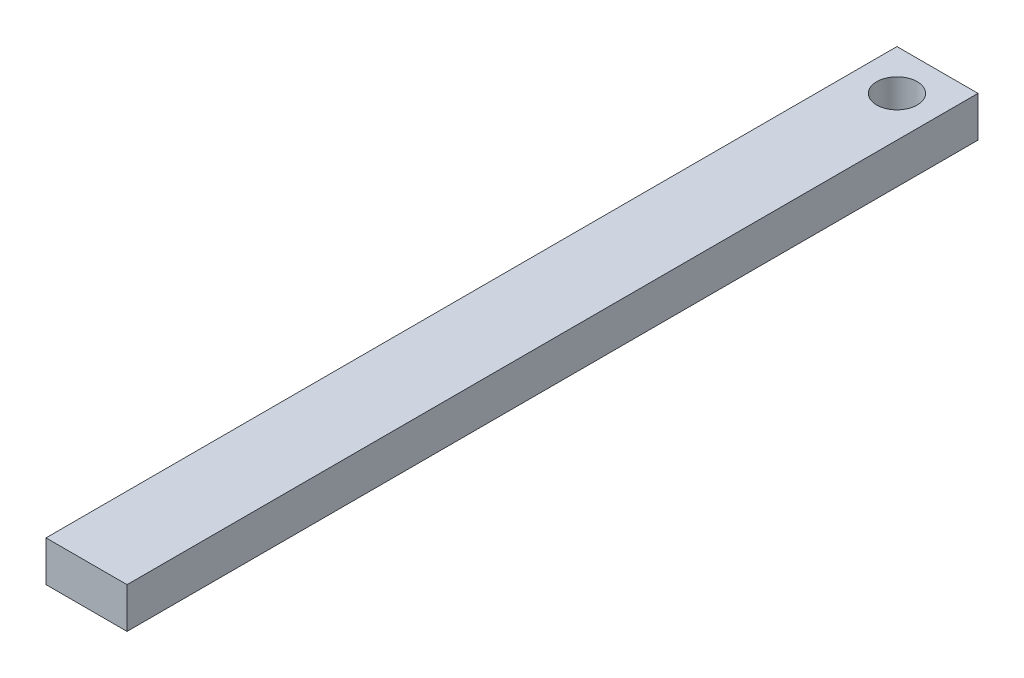
SolidWorks part; units mm, degrees
ref_plane "Front Plane" through (0, 0, 0) normal (0, 0, 1) x (1, 0, 0)
ref_plane "Top Plane" through (0, 0, 0) normal (0, 1, 0) x (1, 0, 0)
ref_plane "Right Plane" through (0, 0, 0) normal (1, 0, 0) x (0, 0, -1)
sketch "Sketch1" plane through (0, 0, 0) normal (0, 1, 0) x (1, 0, 0)
  line L0 (0, 26.1364) -> (0, -221.3977) construction
  line L1 (-30.9091, 0) -> (36.7424, 0) construction
  line L2 (10, 0) -> (-10, 0)
  line L3 (-10, 0) -> (-10, -210)
  line L4 (-10, -210) -> (10, -210)
  line L5 (10, 0) -> (10, -210)
  point P8 (0, -221.3977)
  point P11 (0, -210)
  point P12 (0, 0)
  dimension "D1" = 10
  dimension "D2" = 210
extrude "Boss-Extrude2" add sketch "Sketch1" along normal blind 10
sketch "Sketch2" plane through (0, 10, 0) normal (0, 1, 0) x (1, 0, 0)
  line L0 (0, 75.8702) -> (0, -81.1904) construction
  line L1 (-64.4685, 0) -> (90.0752, 0) construction
  circle A0 centre (0, -10) radius 5
  dimension "D2" = 10
  dimension "D1" = 10
extrude "Cut-Extrude1" cut sketch "Sketch2" against normal blind 10
